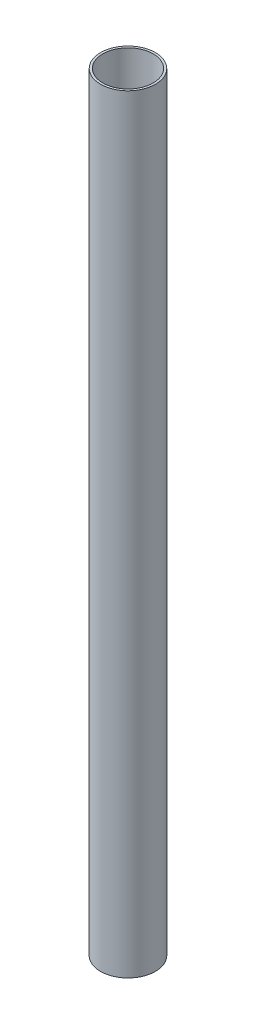
SolidWorks part; units mm, degrees
material "ПВХ 0.007 Смягченный"
ref_plane "Спереди" through (0, 0, 0) normal (0, 0, 1) x (1, 0, 0)
ref_plane "Сверху" through (0, 0, 0) normal (0, 1, 0) x (1, 0, 0)
ref_plane "Справа" through (0, 0, 0) normal (1, 0, 0) x (0, 0, -1)
sketch "Эскиз1" plane through (0, 0, 0) normal (0, 1, 0) x (1, 0, 0)
  circle A0 centre (0, 0) radius 25
  circle A1 centre (0, 0) radius 23
  dimension "ExDBody" = 50
  dimension "InDBody" = 46
extrude "Бобышка-Вытянуть1" add sketch "Эскиз1" along normal blind 700
